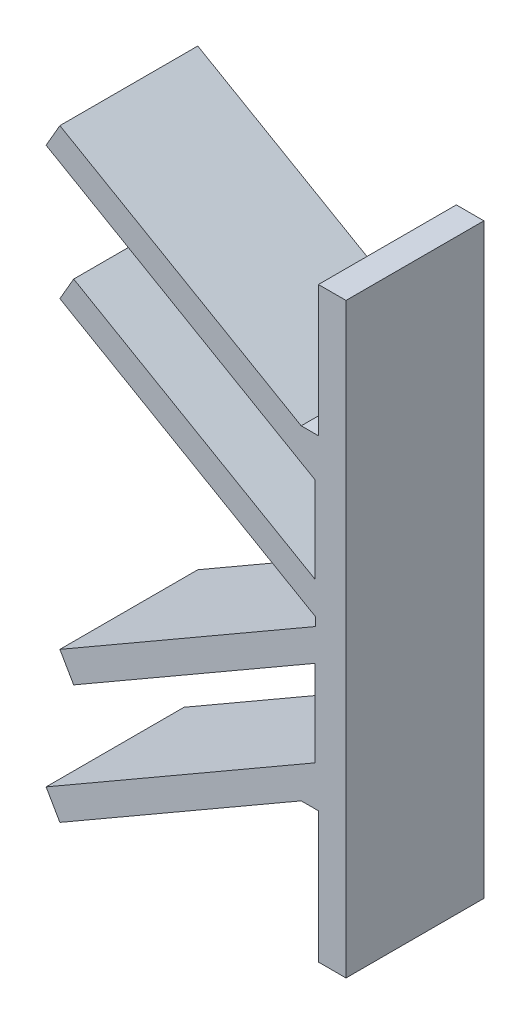
SolidWorks part; units mm, degrees
ref_plane "Front Plane" through (0, 0, 0) normal (1, 0, 0) x (0, 1, 0)
ref_plane "Top Plane" through (0, 0, 0) normal (0, 0, 1) x (0, 1, 0)
ref_plane "Right Plane" through (0, 0, 0) normal (0, 1, 0) x (-1, 0, 0)
sketch "Sketch1" plane through (0, 0, 0) normal (0, 0, 1) x (0, 1, 0)
  line L0 (-16.6, -1.8) -> (-16.6, -0.2)
  line L1 (-16.6, -0.2) -> (-9, -0.2)
  line L2 (-9, -0.2) -> (-9, 0.8)
  line L3 (-9, 0.8) -> (-17.0829, 14.8)
  line L4 (-15.6973, 15.6) -> (-6.6906, 0)
  line L5 (-6.6906, 0) -> (-1.6906, 0)
  line L6 (-1.6906, 0) -> (-9.7735, 14)
  line L7 (-7.9357, 14.0169) -> (0.172, -0.0262)
  line L8 (0.172, -0.0262) -> (0.672, -0.0262)
  line L18 (0.422, -0.0262) -> (0.422, 5.2049) construction
  line L19 (-17.0829, 14.8) -> (-15.6973, 15.6)
  line L20 (-9.7735, 14) -> (-7.9357, 14.0169) construction
  line L21 (-9.7735, 14) -> (-8.3879, 14.8)
  line L22 (-8.3879, 14.8) -> (-7.9357, 14.0169)
  line L23 (10.6176, 14) -> (8.7798, 14.0169) construction
  line L40 (9.2319, 14.8) -> (8.7798, 14.0169)
  line L41 (10.6176, 14) -> (9.2319, 14.8)
  line L42 (17.927, 14.8) -> (16.5413, 15.6)
  line L43 (8.7798, 14.0169) -> (0.672, -0.0262)
  line L44 (2.5347, 0) -> (10.6176, 14)
  line L45 (7.5347, 0) -> (2.5347, 0)
  line L46 (16.5413, 15.6) -> (7.5347, 0)
  line L47 (9.8441, 0.8) -> (17.927, 14.8)
  line L48 (9.8441, -0.2) -> (9.8441, 0.8)
  line L49 (17.4441, -0.2) -> (9.8441, -0.2)
  line L50 (-16.6, -1.8) -> (0.422, -1.8)
  line L51 (17.4441, -0.2) -> (17.4441, -1.8)
  line L52 (17.4441, -1.8) -> (0.422, -1.8)
  point P21 (0.4, -1.8)
  dimension "D1" = 14
  dimension "D2" = 1.6
  dimension "D3" = 1
  dimension "D6" = 60
  dimension "D7" = 1.6
  dimension "D8" = 1.6
  dimension "D9" = 5
  dimension "D10" = 14
  dimension "D12" = 7.6
extrude "Boss-Extrude1" add sketch "Sketch1" along normal blind 8
